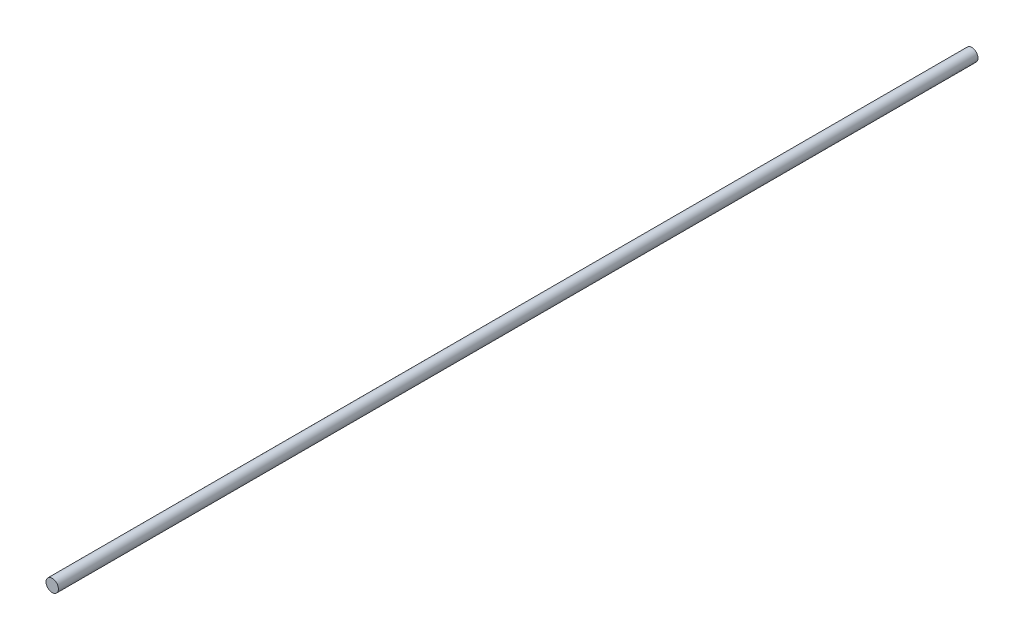
SolidWorks part; units mm, degrees
ref_plane "Plan de face" through (0, 0, 0) normal (0, 0, 1) x (1, 0, 0)
ref_plane "Plan de dessus" through (0, 0, 0) normal (0, 1, 0) x (1, 0, 0)
ref_plane "Plan de droite" through (0, 0, 0) normal (1, 0, 0) x (0, 0, -1)
sketch "Esquisse1" plane through (0, 0, 0) normal (0, 0, 1) x (1, 0, 0)
  circle A0 centre (0, 0) radius 5
  dimension "D1" = 10
extrude "Boss.-Extru.1" add sketch "Esquisse1" along normal blind 740
